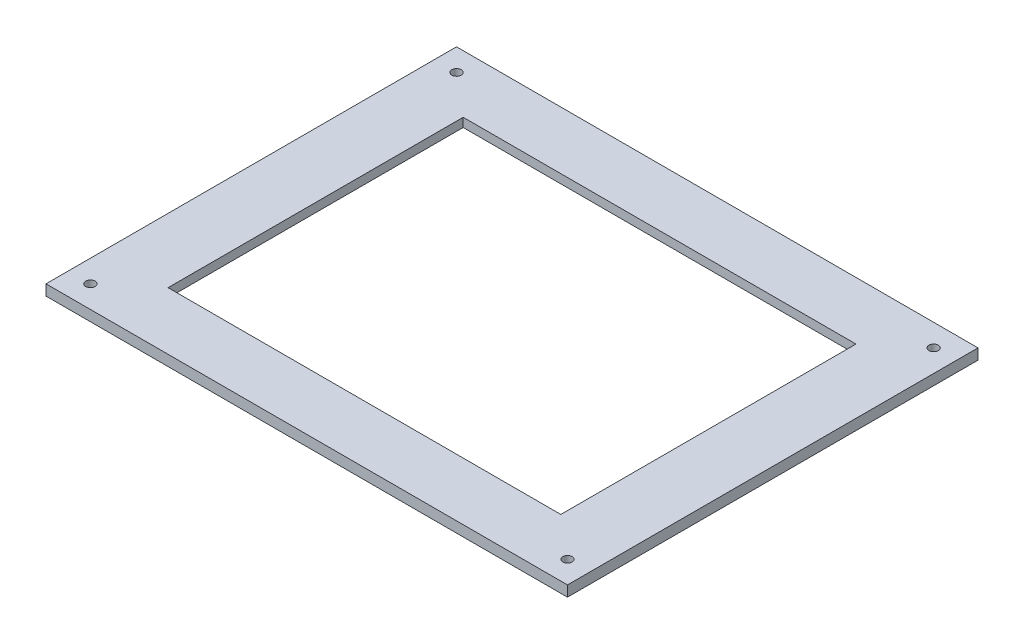
SolidWorks part; units mm, degrees
ref_plane "Alzado" through (0, 0, 0) normal (0, 0, 1) x (1, 0, 0)
ref_plane "Planta" through (0, 0, 0) normal (0, 1, 0) x (1, 0, 0)
ref_plane "Vista lateral" through (0, 0, 0) normal (1, 0, 0) x (0, 0, -1)
sketch "Croquis1" plane through (0, 0, 0) normal (0, 1, 0) x (1, 0, 0)
  line L1 (117.5, -92.5) -> (-117.5, -92.5)
  line L2 (117.5, -92.5) -> (117.5, 92.5)
  line L3 (117.5, 92.5) -> (-117.5, 92.5)
  line L4 (-117.5, -92.5) -> (-117.5, 92.5)
  line L5 (117.5, -92.5) -> (-117.5, 92.5) construction
  line L6 (117.5, 92.5) -> (-117.5, -92.5) construction
  line L7 (88.5, -66.5) -> (-88.5, -66.5)
  line L8 (88.5, -66.5) -> (88.5, 66.5)
  line L9 (88.5, 66.5) -> (-88.5, 66.5)
  line L10 (-88.5, -66.5) -> (-88.5, 66.5)
  line L11 (88.5, -66.5) -> (-88.5, 66.5) construction
  line L12 (88.5, 66.5) -> (-88.5, -66.5) construction
  point P0 (0, 0)
  point P6 (0, 0)
  dimension "D1" = 235
  dimension "D2" = 185
  dimension "D3" = 133
  dimension "D4" = 177
extrude "Saliente-Extruir1" add sketch "Croquis1" along normal blind 4
sketch "Croquis2" plane through (0, 0, 0) normal (0, -1, 0) x (1, 0, 0)
  line L1 (94, -71) -> (-94, -71)
  line L2 (94, -71) -> (94, 71)
  line L3 (94, 71) -> (-94, 71)
  line L4 (-117.5, 92.5) -> (-117.5, -92.5)
  line L5 (-117.5, -92.5) -> (117.5, -92.5)
  line L6 (117.5, -92.5) -> (117.5, 92.5)
  line L7 (117.5, 92.5) -> (-117.5, 92.5)
  line L8 (-117.5, 92.5) -> (-117.5, -92.5)
  line L9 (-117.5, -92.5) -> (117.5, -92.5)
  line L10 (117.5, -92.5) -> (117.5, 92.5)
  line L11 (117.5, 92.5) -> (-117.5, 92.5)
  line L12 (-94, -71) -> (-94, 71)
  line L13 (94, -71) -> (-94, 71) construction
  line L14 (94, 71) -> (-94, -71) construction
  point P2 (0, 0)
  dimension "D2" = 142
  dimension "D3" = 188
  dimension "D1" = 0
extrude "Saliente-Extruir2" add sketch "Croquis2" along normal blind 0.8
sketch "Croquis3" plane through (0, 4, 0) normal (0, 1, 0) x (1, 0, 0)
  line L0 (0, 0) -> (-117.5, 0) construction
  line L1 (-117.5, 82.5) -> (-107.5, 82.5) construction
  line L2 (-107.5, 82.5) -> (-107.5, 92.5) construction
  line L3 (0, 0) -> (0, 92.5) construction
  line L4 (-117.5, 92.5) -> (-117.5, -92.5)
  line L5 (-117.5, -92.5) -> (117.5, -92.5)
  line L6 (117.5, -92.5) -> (117.5, 92.5)
  line L7 (117.5, 92.5) -> (-117.5, 92.5)
  line L8 (-117.5, 92.5) -> (-117.5, -92.5)
  line L9 (-117.5, -92.5) -> (117.5, -92.5)
  line L10 (117.5, -92.5) -> (117.5, 92.5)
  line L11 (117.5, 92.5) -> (-117.5, 92.5)
  circle A1 centre (-107.5, 82.5) radius 2.125
  circle A2 centre (-107.5, -82.5) radius 2.125
  circle A3 centre (107.5, -82.5) radius 2.125
  circle A4 centre (107.5, 82.5) radius 2.125
  dimension "D4" = 4.25
  dimension "D2" = 10
  dimension "D3" = 10
  dimension "D1" = 0
extrude "Cortar-Extruir1" cut sketch "Croquis3" against normal blind 5 contours A1 | A2 | A4 | A3
sketch "Croquis4" plane through (0, -0.8, 0) normal (0, -1, 0) x (1, 0, 0)
  line L0 (-94, 71) -> (-94, -71) construction
  line L1 (-94, 11) -> (-94, -11)
  line L2 (94, -71) -> (94, 71) construction
  line L3 (94, -11) -> (94, 11)
  line L4 (117.5, 92.5) -> (-117.5, 92.5)
  line L5 (-117.5, 92.5) -> (-117.5, -92.5)
  line L6 (-117.5, -92.5) -> (117.5, -92.5)
  line L7 (117.5, -92.5) -> (117.5, 92.5)
  line L8 (117.5, 92.5) -> (-117.5, 92.5)
  line L9 (-117.5, 92.5) -> (-117.5, -92.5)
  line L10 (-117.5, -92.5) -> (117.5, -92.5)
  line L11 (117.5, -92.5) -> (117.5, 92.5)
  line L12 (-117.5, 0) -> (117.5, 0) construction
  line L13 (-94, 11) -> (-106, 11)
  line L14 (-106, 11) -> (-106, -11)
  line L15 (-106, -11) -> (-94, -11)
  line L16 (94, 11) -> (106, 11)
  line L17 (106, 11) -> (106, -11)
  line L18 (106, -11) -> (94, -11)
  line M20 (-94, -71) -> (-94, 71)
  line M22 (94, 71) -> (94, -71)
  dimension "D2" = 12
  dimension "D3" = 11
  dimension "D4" = 11
  dimension "D5" = 12
  dimension "D6" = 11
  dimension "D1" = 0
extrude "Cortar-Extruir2" cut sketch "Croquis4" against normal blind 1.2 contours L14 L12 L1 L13 | L12 L14 L15 M20 | L12 L17 L16 M22 | L12 L3 L18 L17
